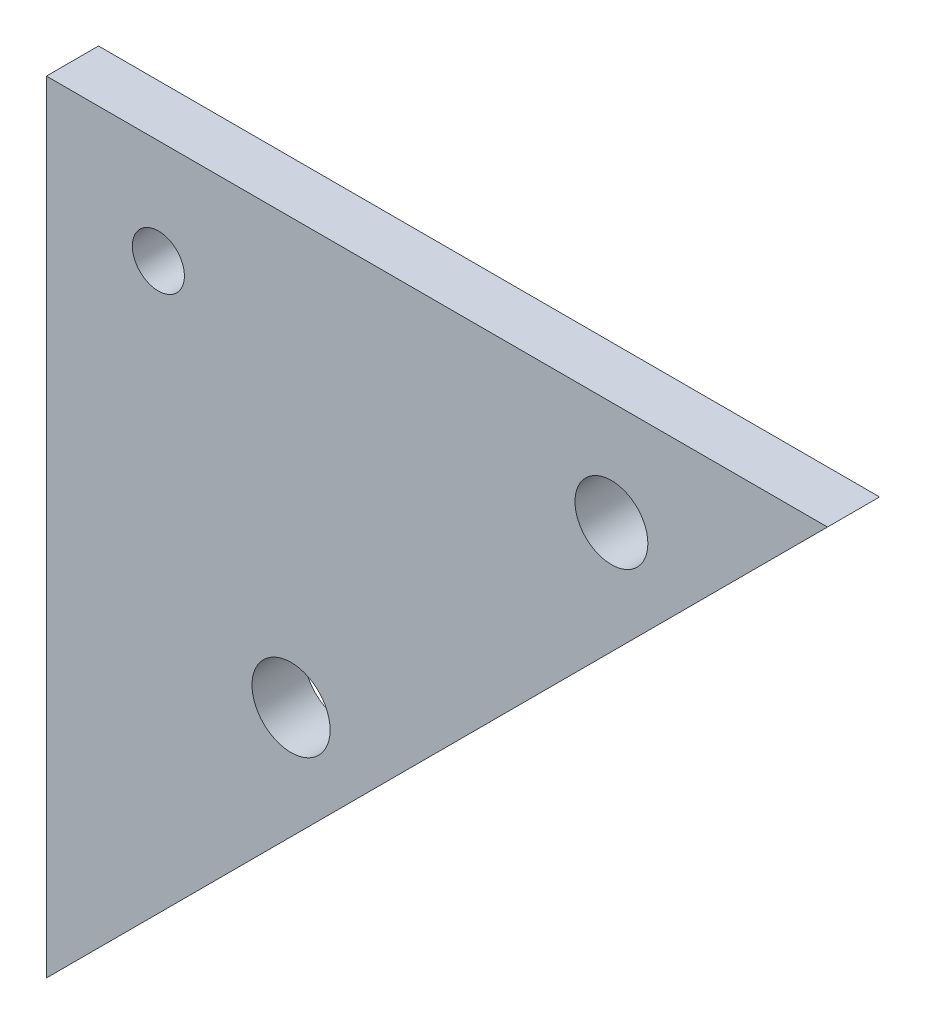
SolidWorks part; units mm, degrees
ref_plane "Front Plane" through (0, 0, 0) normal (0, 0, 1) x (1, 0, 0)
ref_plane "Top Plane" through (0, 0, 0) normal (0, 1, 0) x (1, 0, 0)
ref_plane "Right Plane" through (0, 0, 0) normal (1, 0, 0) x (0, 0, -1)
sketch "Sketch1" plane through (0, 0, 0) normal (0, 0, 1) x (1, 0, 0)
  line L0 (-38.1, 24.5752) -> (-38.1, -13.5248)
  line L3 (0, 24.5752) -> (-38.1, 24.5752)
  line L5 (-38.1, -13.5248) -> (0, 24.5752)
  point P0 (-19.05, 24.5752)
  dimension "D1" = 38.1
  dimension "D2" = 38.1
  dimension "D3" = 90
extrude "Boss-Extrude1" add sketch "Sketch1" along normal blind 2.54 contours L5 L3 L0
sketch "Sketch2" plane through (0, 0, 2.54) normal (0, 0, 1) x (1, 0, 0)
  line L1 (0, 24.5752) -> (-38.1, 24.5752) construction
  line L2 (-5.08, 19.4952) -> (-38.1, 19.4952) construction
  line L3 (-10.541, 19.4952) -> (-32.639, 19.4952) construction
  line L6 (-38.1, -13.5248) -> (0, 24.5752) construction
  line L7 (-38.1, 24.5752) -> (-38.1, -13.5248) construction
  line L8 (-10.541, 19.4952) -> (-26.1666, 3.8695) construction
  circle A0 centre (-32.639, 19.4952) radius 1.27
  circle A1 centre (-10.541, 19.4952) radius 1.778
  circle A2 centre (-26.1666, 3.8695) radius 1.905
  point P4 (-21.59, 19.4952)
  point P5 (-21.59, 19.4952)
  point P8 (-19.05, 24.5752)
  point P14 (-21.59, 19.4952)
  dimension "D4" = 2.54
  dimension "D1" = 3.556
  dimension "D6" = 3.81
  dimension "D2" = 22.098
  dimension "D3" = 5.08
  dimension "D5" = 22.098
extrude "Cut-Extrude1" cut sketch "Sketch2" against normal through all
equation "\"D5@Sketch2\"=\"D2@Sketch2\""
